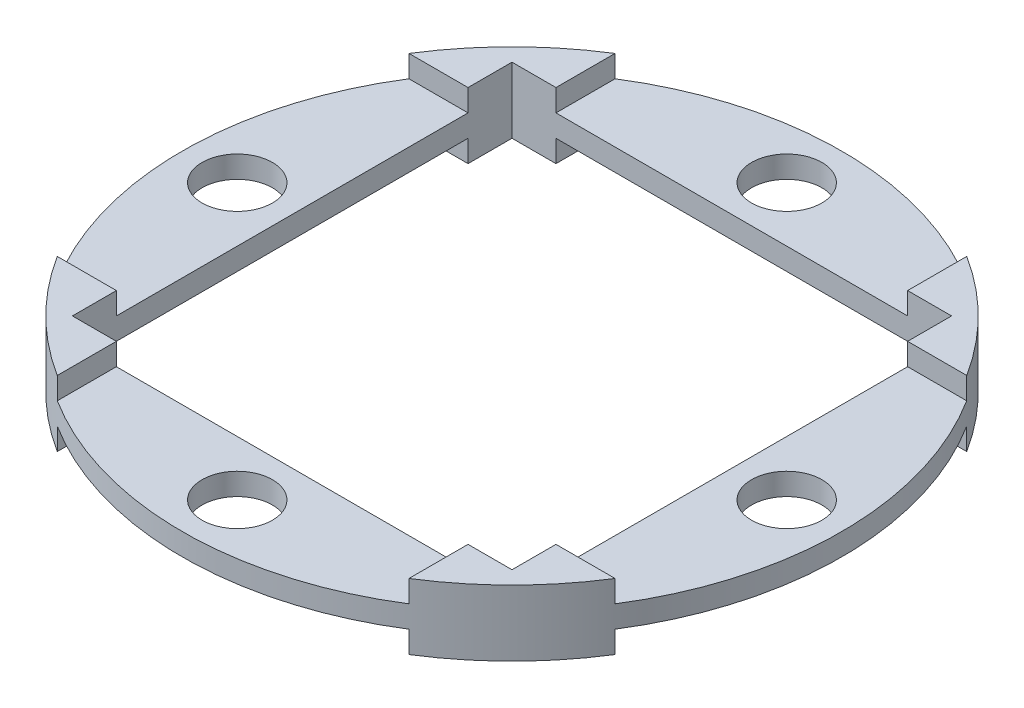
SolidWorks part; units mm, degrees
material "Custom Plastic"
ref_plane "Front Plane" through (0, 0, 0) normal (0, 0, 1) x (1, 0, 0)
ref_plane "Top Plane" through (0, 0, 0) normal (0, 1, 0) x (1, 0, 0)
ref_plane "Right Plane" through (0, 0, 0) normal (1, 0, 0) x (0, 0, -1)
sketch "Sketch1" plane through (0, 0, 0) normal (0, 1, 0) x (1, 0, 0)
  line L0 (0, 0) -> (0, -17.9724) construction
  line L1 (-50, -50) -> (50, -50)
  line L2 (-50, -50) -> (-50, 50)
  line L3 (-50, 50) -> (50, 50)
  line L4 (50, -50) -> (50, 50)
  line L5 (-50, -50) -> (50, 50) construction
  line L6 (-50, 50) -> (50, -50) construction
  line L7 (0, 0) -> (14.9739, 0) construction
  line L8 (0, 62.5) -> (14.3316, 62.5) construction
  line L9 (0, 75) -> (25.822, 75) construction
  circle A0 centre (0, 0) radius 75
  circle A1 centre (0, 0) radius 62.5 construction
  circle A2 centre (0, 62.5) radius 5
  circle A3 centre (62.5, 0) radius 5
  circle A4 centre (0, -62.5) radius 5
  circle A5 centre (-62.5, 0) radius 5
  dimension "D1" = 150
  dimension "D4" = 125
  dimension "D5" = 10
  dimension "D2" = 100
  dimension "D3" = 100
extrude "Boss-Extrude1" add sketch "Sketch1" along normal blind 5 contours A0 | L2 L1 L4 L3
sketch "Sketch2" plane through (0, 5, 0) normal (0, 1, 0) x (1, 0, 0)
  circle A0 centre (0, 0) radius 62.5 construction
  circle A1 centre (-62.5, 0) radius 8
  circle A2 centre (0, 62.5) radius 8
  circle A3 centre (62.5, 0) radius 8
  circle A4 centre (0, -62.5) radius 8
  dimension "D1" = 125
  dimension "D3" = 16
extrude "Cut-Extrude1" cut sketch "Sketch2" against normal blind 10
sketch "Sketch3" plane through (0, 5, 0) normal (0, 1, 0) x (1, 0, 0)
  line L0 (-50, -50) -> (-40, -50)
  line L3 (-40, -50) -> (-50, -50)
  line L4 (-50, -40) -> (-50, -50)
  line L5 (0, 0) -> (-85.3726, 0) construction
  line L6 (-50, 40) -> (-63.4429, 40)
  line L7 (-50, -50) -> (-50, -40)
  line L8 (-50, -40) -> (-63.4429, -40)
  line L9 (-40, -50) -> (-40, -63.4429)
  line L10 (-50, 40) -> (-50, 50)
  line L11 (-50, 50) -> (-40, 50)
  line L12 (-40, 50) -> (-40, 63.4429)
  line L13 (0, 0) -> (0, -29.0709) construction
  line L14 (50, 40) -> (50, 50)
  line L15 (50, 50) -> (40, 50)
  line L16 (40, 50) -> (40, 63.4429)
  line L17 (50, 40) -> (63.4429, 40)
  line L18 (50, -50) -> (40, -50)
  line L19 (50, -40) -> (50, -50)
  line L20 (50, -40) -> (63.4429, -40)
  line L21 (40, -50) -> (40, -63.4429)
  arc A0 (-63.4429, -40) -> (-40, -63.4429) centre (0, 0) ccw
  arc A2 (-63.4429, 40) -> (-40, 63.4429) centre (0, 0) cw
  arc A3 (63.4429, 40) -> (40, 63.4429) centre (0, 0) ccw
  arc A4 (63.4429, -40) -> (40, -63.4429) centre (0, 0) cw
  line M11 (-50, 50) -> (50, 50)
  line M12 (50, 50) -> (50, -50)
  line M13 (50, -50) -> (-50, -50)
  line M14 (-50, -50) -> (-50, 50)
  circle M15 centre (0, 0) radius 75
  dimension "D3" = 75
  dimension "D1" = 10
  dimension "D2" = 10
extrude "Boss-Extrude2" add sketch "Sketch3" along normal blind 5 contours L21 L20 M13 M15 M12 | L9 L8 M13 M14 M15 | L12 L6 M11 M15 M14 | L17 L16 M12 M15 M11
sketch "Sketch4" plane through (0, 10, 0) normal (0, 1, 0) x (1, 0, 0)
  line L0 (-40, -63.4429) -> (-40, -50) construction
  line L1 (-40, -50) -> (-50, -50) construction
  line L2 (-50, -50) -> (-50, -40) construction
  line L3 (-50, -40) -> (-63.4429, -40) construction
  line L4 (50, 50) -> (50, 40)
  line L5 (50, 40) -> (63.4429, 40)
  line L6 (40, 63.4429) -> (40, 50)
  line L7 (40, 50) -> (50, 50)
  line L8 (50, 50) -> (50, 40)
  line L9 (50, 40) -> (63.4429, 40)
  line L10 (40, 63.4429) -> (40, 50)
  line L11 (40, 50) -> (50, 50)
  line L12 (-50, 50) -> (-40, 50)
  line L13 (-40, 50) -> (-40, 63.4429)
  line L14 (-63.4429, 40) -> (-50, 40)
  line L15 (-50, 40) -> (-50, 50)
  line L16 (-50, 50) -> (-40, 50)
  line L17 (-40, 50) -> (-40, 63.4429)
  line L18 (-63.4429, 40) -> (-50, 40)
  line L19 (-50, 40) -> (-50, 50)
  line L20 (50, -50) -> (40, -50) construction
  line L21 (40, -50) -> (40, -63.4429) construction
  line L22 (63.4429, -40) -> (50, -40) construction
  line L23 (50, -40) -> (50, -50) construction
  line L24 (-40, -63.4429) -> (-40, -50)
  line L25 (-40, -50) -> (-50, -50)
  line L26 (-50, -50) -> (-50, -40)
  line L27 (-50, -40) -> (-63.4429, -40)
  line L28 (50, -50) -> (40, -50)
  line L29 (40, -50) -> (40, -63.4429)
  line L30 (63.4429, -40) -> (50, -40)
  line L31 (50, -40) -> (50, -50)
  arc A2 (-63.4429, -40) -> (-40, -63.4429) centre (0, 0) ccw construction
  arc A3 (40, -63.4429) -> (63.4429, -40) centre (0, 0) ccw construction
  arc A4 (63.4429, 40) -> (40, 63.4429) centre (0, 0) ccw
  arc A5 (63.4429, 40) -> (40, 63.4429) centre (0, 0) ccw
  arc A6 (-40, 63.4429) -> (-63.4429, 40) centre (0, 0) ccw
  arc A7 (-40, 63.4429) -> (-63.4429, 40) centre (0, 0) ccw
  arc A8 (-63.4429, -40) -> (-40, -63.4429) centre (0, 0) ccw
  arc A9 (40, -63.4429) -> (63.4429, -40) centre (0, 0) ccw
  dimension "D1" = 0
  dimension "D2" = 0
extrude "Boss-Extrude4" add sketch "Sketch4" against normal blind 15
